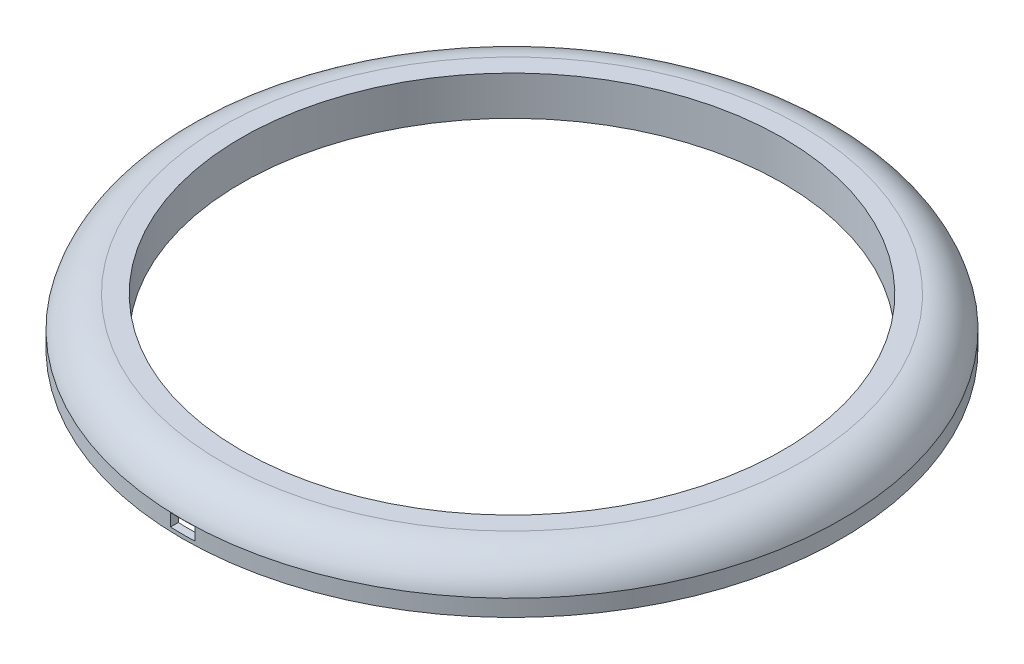
SolidWorks part; units mm, degrees
ref_plane "Front" through (0, 0, 0) normal (0, 0, 1) x (1, 0, 0)
ref_plane "Top" through (0, 0, 0) normal (0, 1, 0) x (1, 0, 0)
ref_plane "Right" through (0, 0, 0) normal (1, 0, 0) x (0, 0, -1)
sketch "Эскиз1" plane through (0, 0, 0) normal (1, 0, 0) x (0, 0, -1)
  line L0 (0, 0) -> (0, 10.6829) construction
  line L1 (36, 0) -> (36, 3)
  line L2 (36, 3) -> (38, 3)
  line L3 (41, -1) -> (42, -1)
  line L4 (36, 0) -> (34.5, 0)
  line L5 (34.5, 0) -> (34.5, 5)
  line L6 (34.5, 5) -> (37, 5)
  line L7 (41, -1) -> (41, 1)
  line L8 (42, -1) -> (42, 1.1152)
  arc A0 (42, 1.1152) -> (37, 5) centre (37, -0.1601) ccw
  arc A1 (41, 1) -> (38, 3) centre (38.0397, -0.1904) ccw
  dimension "D1" = 1.5
  dimension "D2" = 3
  dimension "D3" = 2
  dimension "D4" = 5
  dimension "D5" = 6
  dimension "D6" = 1
  dimension "D7" = 2.5
  dimension "D8" = 1
  dimension "D9" = 36
revolve "Повернуть1" add sketch "Эскиз1" angle 360 about L0
ref_plane "Плоскость1" through (0, 0, -42) normal (0, 0, -1) x (-1, 0, 0)
sketch "Эскиз2" plane through (0, 0, -42) normal (0, 0, -1) x (-1, 0, 0)
  line L0 (-42, -1) -> (42, -1) construction
  line L1 (-1.55, 1.1) -> (1.55, 1.1)
  line L2 (-1.55, 1.1) -> (-1.55, -0.5)
  line L3 (-1.55, -0.5) -> (1.55, -0.5)
  line L4 (1.55, 1.1) -> (1.55, -0.5)
  line L5 (-1.55, 1.1) -> (1.55, -0.5) construction
  line L6 (-1.55, -0.5) -> (1.55, 1.1) construction
  point P0 (0, 0.3)
  dimension "D1" = 1.6
  dimension "D2" = 3.1
  dimension "D3" = 0.5
  dimension "D4" = 0
extrude "Вырез-Вытянуть1" cut sketch "Эскиз2" against normal blind 5
pattern_circular "Круговой массив2" count 2 over 360 about axis through (0, 0, 0) along (0, -1, 0) of "Вырез-Вытянуть1"
